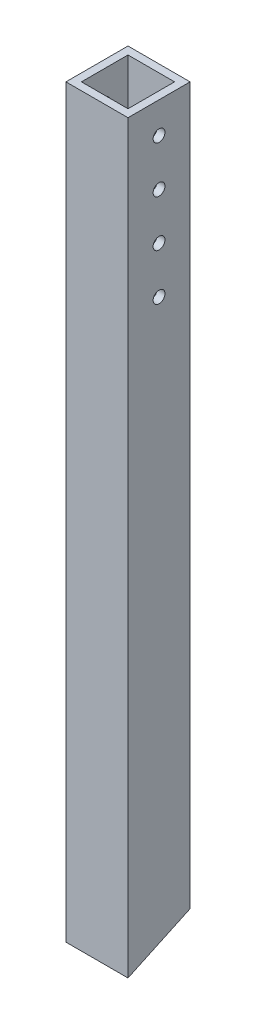
SolidWorks part; units mm, degrees
material "6061-T6 (SS)"
ref_plane "Front" through (0, 0, 0) normal (0, 0, 1) x (1, 0, 0)
ref_plane "Top" through (0, 0, 0) normal (0, 1, 0) x (1, 0, 0)
ref_plane "Right" through (0, 0, 0) normal (1, 0, 0) x (0, 0, -1)
sketch "Sketch1" plane through (0, 0, 0) normal (0, 1, 0) x (1, 0, 0)
  line L0 (-9.525, -9.525) -> (-9.525, 9.525)
  line L1 (-12.7, -12.7) -> (12.7, -12.7)
  line L2 (-12.7, -12.7) -> (-12.7, 12.7)
  line L3 (-12.7, 12.7) -> (12.7, 12.7)
  line L4 (12.7, -12.7) -> (12.7, 12.7)
  line L5 (-12.7, -12.7) -> (12.7, 12.7) construction
  line L6 (-12.7, 12.7) -> (12.7, -12.7) construction
  line L7 (-9.525, 9.525) -> (9.525, 9.525)
  line L8 (9.525, -9.525) -> (9.525, 9.525)
  line L9 (-9.525, -9.525) -> (9.525, -9.525)
  point P0 (0, 0)
  dimension "D1" = 25.4
  dimension "D2" = 3.175
extrude "Boss-Extrude1" add sketch "Sketch1" along normal blind 304.8
sketch "Sketch2" plane through (12.7, 0, 0) normal (1, 0, 0) x (0, 0, -1)
  line L0 (-12.7, 304.8) -> (12.7, 304.8) construction
  line L1 (0, 292.1) -> (0, 273.05) construction
  line L3 (-12.7, 0) -> (12.7, 11.8442)
  line L4 (12.7, 304.8) -> (12.7, 0) construction
  line L5 (12.7, 11.8442) -> (12.7, 0)
  line L6 (12.7, 0) -> (-12.7, 0)
  circle A0 centre (0, 292.1) radius 2.413
  circle A1 centre (0, 273.05) radius 2.413
  circle A2 centre (0, 254) radius 2.413
  circle A3 centre (0, 234.95) radius 2.413
  dimension "D1" = 4.826
  dimension "D2" = 12.7
  dimension "D4" = 19.05
  dimension "D5" = 25
  dimension "D3" = 4
extrude "Cut-Extrude1" cut sketch "Sketch2" against normal blind 25.4
